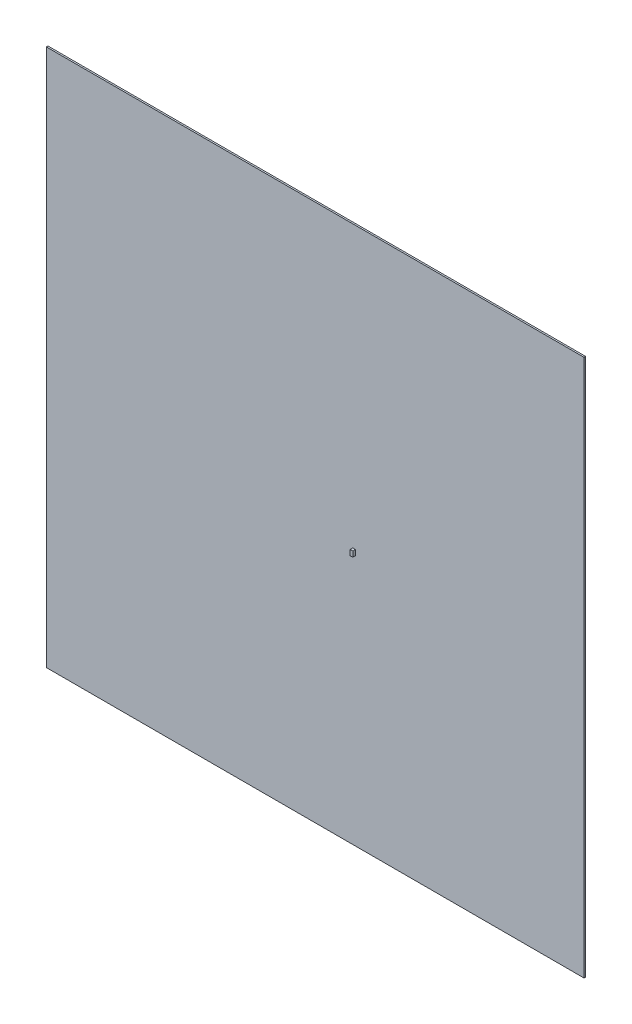
SolidWorks part; units mm, degrees
ref_plane "正面" through (0, 0, 0) normal (0, 0, 1) x (1, 0, 0)
ref_plane "平面" through (0, 0, 0) normal (0, 1, 0) x (1, 0, 0)
ref_plane "右側面" through (0, 0, 0) normal (1, 0, 0) x (0, 0, -1)
sketch "ｽｹｯﾁ1" plane through (0, 0, 0) normal (0, 0, 1) x (1, 0, 0)
  line L1 (0, 0) -> (10000, 0)
  line L2 (0, 0) -> (0, 10000)
  line L3 (0, 10000) -> (10000, 10000)
  line L4 (10000, 0) -> (10000, 10000)
  dimension "D1" = 10000
  dimension "D2" = 10000
extrude "ﾎﾞｽ - 押し出し1" add sketch "ｽｹｯﾁ1" along normal blind 30
sketch "ｽｹｯﾁ2" plane through (0, 0, 30) normal (0, 0, 1) x (1, 0, 0)
  line L1 (5749.1275, 4678.0252) -> (5699.1275, 4678.0252)
  line L2 (5749.1275, 4678.0252) -> (5749.1275, 4778.0252)
  line L3 (5749.1275, 4778.0252) -> (5699.1275, 4778.0252)
  line L4 (5699.1275, 4678.0252) -> (5699.1275, 4778.0252)
  line L5 (5749.1275, 4678.0252) -> (5699.1275, 4778.0252) construction
  line L6 (5749.1275, 4778.0252) -> (5699.1275, 4678.0252) construction
  point P0 (5724.1275, 4728.0252)
  dimension "D1" = 100
  dimension "D2" = 50
extrude "ﾎﾞｽ - 押し出し2" add sketch "ｽｹｯﾁ2" along normal blind 50
